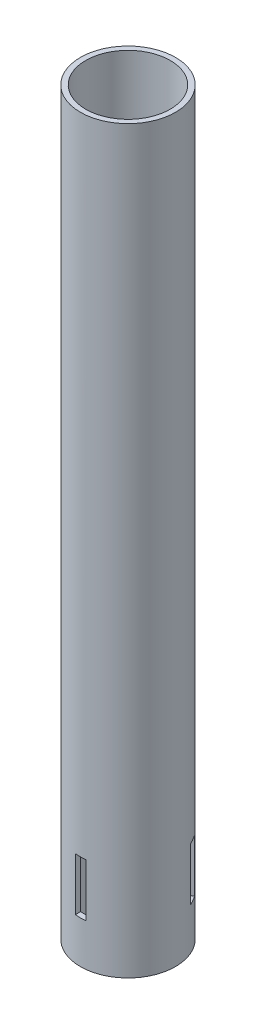
SolidWorks part; units mm, degrees
material "PVC Rigid"
ref_plane "Front Plane" through (0, 0, 0) normal (0, 0, 1) x (1, 0, 0)
ref_plane "Top Plane" through (0, 0, 0) normal (0, 1, 0) x (1, 0, 0)
ref_plane "Right Plane" through (0, 0, 0) normal (1, 0, 0) x (0, 0, -1)
sketch "Sketch1" plane through (0, 0, 0) normal (0, 1, 0) x (1, 0, 0)
  circle A0 centre (0, 0) radius 45
  circle A1 centre (0, 0) radius 40
  dimension "D1" = 80
  dimension "D2" = 5
extrude "Boss-Extrude2" add sketch "Sketch1" along normal blind 700 contours A1
sketch "Sketch2" plane through (0, 0, 0) normal (0, 0, 1) x (1, 0, 0)
  line L0 (0, 0) -> (0, 20.4478)
  line L1 (49.5, 0) -> (-49.5, 0) construction
  line L2 (-5, 40) -> (5, 40)
  line L3 (-5, 40) -> (-5, 90)
  line L4 (-5, 90) -> (5, 90)
  line L5 (5, 40) -> (5, 90)
  line L6 (-5, 40) -> (5, 90) construction
  line L7 (-5, 90) -> (5, 40) construction
  point P3 (0, 65)
  dimension "D1" = 50
  dimension "D2" = 10
  dimension "D3" = 40
extrude "Cut-Extrude4" cut sketch "Sketch2" along normal blind 62 contours L5 L4 L3 L2
pattern_circular "CirPattern1" count 3 over 360 about axis through (0, 0, 0) along (0, 1, 0) of "Cut-Extrude4"
